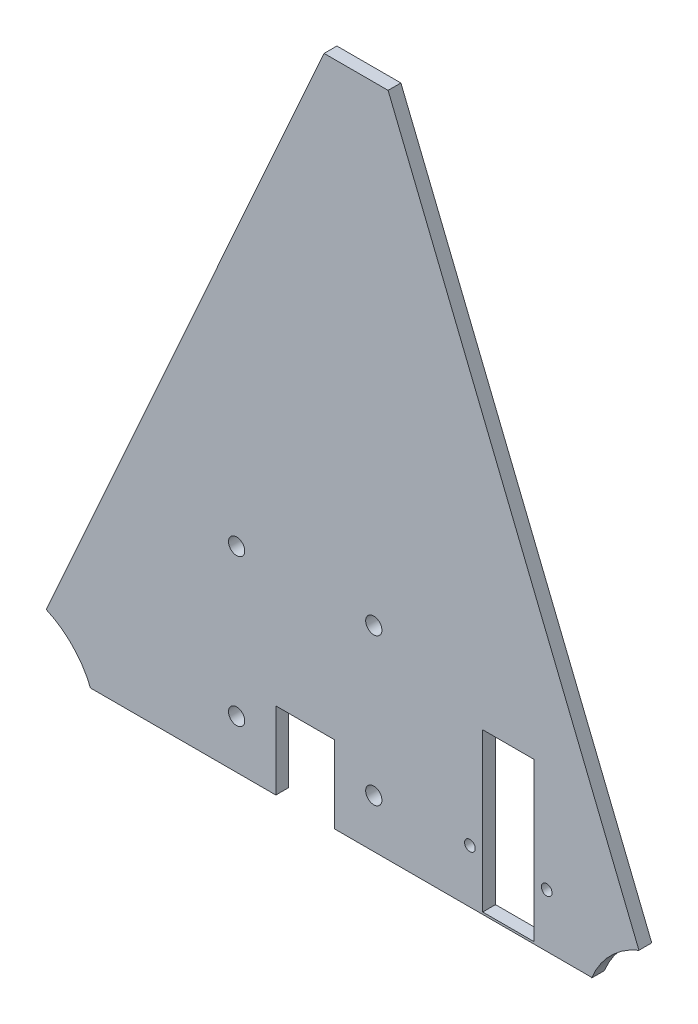
SolidWorks part; units mm, degrees
ref_plane "Front Plane" through (0, 0, 0) normal (0, 0, 1) x (1, 0, 0)
ref_plane "Top Plane" through (0, 0, 0) normal (0, 1, 0) x (1, 0, 0)
ref_plane "Right Plane" through (0, 0, 0) normal (1, 0, 0) x (0, 0, -1)
sketch "Sketch2" plane through (0, 0, 0) normal (0, 0, 1) x (1, 0, 0)
  line L0 (-189.7401, 245.3834) -> (-375.9085, -170.4146)
  line L1 (-375.9085, -170.4146) -> (16.7755, -170.4146)
  line L2 (16.7755, -170.4146) -> (-151.6401, 245.3834)
  line L4 (-189.7401, 245.3834) -> (-151.6401, 245.3834)
  dimension "D1" = 415.798
  dimension "D2" = 415.798
  dimension "D3" = 67.95
  dimension "D4" = 38.1
  dimension "D5" = 392.684
extrude "Boss-Extrude1" add sketch "Sketch2" along normal blind 7.62 contours L0 L1 L2 L4
sketch "Sketch5" plane through (0, 0, 0) normal (0, 0, -1) x (-1, 0, 0)
  circle A0 centre (375.9085, -170.4146) radius 15.875
  dimension "D1" = 31.75
extrude "Cut-Extrude2" cut sketch "Sketch5" against normal blind 50.8
sketch "Sketch6" plane through (0, 0, 0) normal (0, 0, -1) x (-1, 0, 0)
  circle A0 centre (-16.7755, -170.4146) radius 15.875
  dimension "D1" = 31.75
extrude "Cut-Extrude3" cut sketch "Sketch6" against normal blind 50.8 contours A0
ref_plane "Plane1" through (-360.0335, -170.4146, 0) normal (1, 0, 0) x (0, 0, -1)
sketch "Sketch8" plane through (0, 0, 0) normal (0, 0, -1) x (-1, 0, 0)
  line L0 (254.9716, -43.4146) -> (147.0216, -43.4146) construction
  line L1 (360.0335, -170.4146) -> (-0.9005, -170.4146) construction
  line L2 (254.9716, -170.4146) -> (254.9716, 97.7332) construction
  line L3 (254.9716, -43.4146) -> (254.9716, -170.4146) construction
  line L4 (147.0216, -43.4146) -> (147.0216, -170.4146) construction
  line L5 (147.0216, -170.4146) -> (183.5239, -170.4146) construction
  line L6 (183.5239, -170.4146) -> (183.5239, -105.3906) construction
  line L7 (170.6901, 245.3834) -> (179.5665, -170.4146) construction
  line L8 (189.7401, 245.3834) -> (151.6401, 245.3834) construction
  line L9 (183.5239, -105.3906) -> (218.4489, -105.3906) construction
  line L10 (218.4489, -105.3906) -> (218.4489, -170.4146) construction
  line L11 (218.4489, -170.4146) -> (218.4489, -105.3906)
  line L12 (218.4489, -105.3906) -> (183.5239, -105.3906)
  line L13 (183.5239, -105.3906) -> (183.5239, -170.4146)
  line L14 (153.8492, -170.4146) -> (153.8492, -48.647) construction
  dimension "D1" = 268.1478
  dimension "D2" = 107.95
  dimension "D3" = 127
  dimension "D4" = 36.5023
  dimension "D5" = 65.024
  dimension "D6" = 34.925
  dimension "D7" = 121.7676
extrude "Cut-Extrude4" cut sketch "Sketch8" against normal blind 7.62 and the other way through all contours L11 L12 L13
sketch "Sketch9" plane through (0, 0, 0) normal (0, 0, -1) x (-1, 0, 0)
  line L0 (164.9819, -122.4086) -> (183.5239, -122.4086) construction
  line L1 (183.5239, -170.4146) -> (183.5239, -105.3906) construction
  line L2 (160.1559, -127.2346) -> (160.1559, -170.4146) construction
  line L3 (183.5239, -170.4146) -> (-0.9005, -170.4146) construction
  line L4 (236.9909, -122.4086) -> (218.4489, -122.4086) construction
  line L5 (218.4489, -105.3906) -> (218.4489, -170.4146) construction
  line L6 (241.8169, -127.2346) -> (241.8169, -170.4146) construction
  line L7 (360.0335, -170.4146) -> (218.4489, -170.4146) construction
  circle A0 centre (160.1559, -122.4086) radius 4.826
  circle A1 centre (241.8169, -122.4086) radius 4.826
  dimension "D3" = 9.652
  dimension "D6" = 9.652
  dimension "D1" = 18.542
  dimension "D2" = 43.18
  dimension "D4" = 18.542
  dimension "D5" = 43.18
sketch "Sketch10" plane through (0, 0, 0) normal (0, 0, -1) x (-1, 0, 0)
  line L0 (218.4489, -110.7541) -> (349.1963, -110.7541) construction
  line L1 (218.4489, -105.3906) -> (218.4489, -170.4146) construction
  line L2 (189.7401, 245.3834) -> (369.4213, -155.9256) construction
  line L3 (7.3895, -110.7541) -> (138.1995, -110.7541) construction
  line L4 (-10.8158, -155.7008) -> (151.6401, 245.3834) construction
  line L5 (64.8263, -170.4146) -> (64.8263, -56.1146) construction
  line L8 (183.5239, -170.4146) -> (-0.9005, -170.4146) construction
  line L9 (64.8263, -56.1146) -> (95.3063, -56.1146) construction
  line L11 (95.3063, -56.1146) -> (95.3063, -170.4146) construction
  line L12 (64.8263, -170.4146) -> (64.8263, -56.1146)
  line L13 (64.8263, -56.1146) -> (95.3063, -56.1146)
  line L14 (95.3063, -56.1146) -> (95.3063, -170.4146)
  line L15 (64.8263, -170.4146) -> (95.3063, -170.4146)
  dimension "D1" = 130.7473
  dimension "D2" = 130.81
  dimension "D3" = 114.3
  dimension "D4" = 30.48
extrude "Cut-Extrude6" cut sketch "Sketch9" against normal up to next
extrude "Cut-Extrude12" cut sketch "Sketch10" against normal blind 25.4 contours L13 L14 L15 L12
sketch "Sketch13" plane through (0, 0, 0) normal (0, 0, -1) x (-1, 0, 0)
  line L0 (80.0663, -56.1146) -> (80.0663, -50.7806) construction
  line L1 (64.8263, -56.1146) -> (95.3063, -56.1146) construction
  line L2 (80.0663, -50.7806) -> (80.0663, -45.9546) construction
  circle A0 centre (80.0663, -45.9546) radius 4.826
  dimension "D3" = 9.652
  dimension "D1" = 5.334
  dimension "D2" = 4.826
sketch "Sketch14" plane through (0, 0, 0) normal (0, 0, -1) x (-1, 0, 0)
  circle A0 centre (-16.7755, -170.4146) radius 50.8
  dimension "D1" = 101.6
extrude "Cut-Extrude14" cut sketch "Sketch14" against normal up to next
sketch "Sketch15" plane through (0, 0, 0) normal (0, 0, -1) x (-1, 0, 0)
  circle A0 centre (375.9085, -170.4146) radius 50.8
  dimension "D1" = 101.6
extrude "Cut-Extrude15" cut sketch "Sketch15" against normal up to next
sketch "Sketch16" plane through (0, 0, 0) normal (0, 0, -1) x (-1, 0, 0)
  line L0 (95.3063, -56.1146) -> (95.3063, -170.4146) construction
  line L1 (95.3063, -150.0946) -> (64.8263, -150.0946)
  line L2 (95.3063, -150.0946) -> (95.3063, -170.4146)
  line L3 (95.3063, -170.4146) -> (64.8263, -170.4146)
  line L4 (64.8263, -150.0946) -> (64.8263, -170.4146)
  dimension "D1" = 20.32
extrude "Boss-Extrude2" add sketch "Sketch16" against normal blind 7.62
sketch "Sketch17" plane through (0, 0, 0) normal (0, 0, -1) x (-1, 0, 0)
  line L0 (64.8263, -150.0946) -> (64.8263, -125.9646) construction
  line L1 (64.8263, -150.0946) -> (64.8263, -56.1146) construction
  line L2 (64.8263, -125.9646) -> (64.8263, -113.2646) construction
  line L3 (64.8263, -113.2646) -> (49.5863, -113.2646) construction
  line L4 (49.5863, -113.2646) -> (49.5863, -125.9646) construction
  line L5 (49.5863, -125.9646) -> (64.8263, -125.9646) construction
  line L6 (49.5863, -119.6146) -> (64.8263, -119.6146) construction
  line L7 (95.3063, -113.2646) -> (110.5463, -113.2646) construction
  line L8 (95.3063, -56.1146) -> (95.3063, -150.0946) construction
  line L9 (110.5463, -113.2646) -> (110.5463, -125.9646) construction
  line L10 (110.5463, -125.9646) -> (95.3063, -125.9646) construction
  line L11 (110.5463, -119.6146) -> (95.3063, -119.6146) construction
  circle A0 centre (57.2063, -119.6146) radius 3.175
  circle A3 centre (102.9263, -119.6146) radius 3.175
  dimension "D4" = 6.35
  dimension "D7" = 6.35
  dimension "D1" = 24.13
  dimension "D2" = 12.7
  dimension "D3" = 15.24
  dimension "D5" = 15.24
  dimension "D6" = 12.7
extrude "Cut-Extrude16" cut sketch "Sketch17" against normal up to next
sketch "Sketch18" plane through (0, 0, 0) normal (0, 0, -1) x (-1, 0, 0)
  line L5 (30.4451, -170.4146) -> (331.0546, -170.4146)
  line L6 (30.4451, -170.4146) -> (30.4451, -151.3646)
  line L7 (30.4451, -151.3646) -> (331.0546, -151.3646)
  line L8 (331.0546, -170.4146) -> (331.0546, -151.3646)
  dimension "D1" = 19.05
extrude "Cut-Extrude17" cut sketch "Sketch18" against normal up to next contours L7 L8 L5 L6
sketch "Sketch19" plane through (0, 0, 0) normal (0, 0, -1) x (-1, 0, 0)
  line L0 (241.8169, -122.4086) -> (241.8169, -34.7786) construction
  line L1 (160.1559, -122.4086) -> (160.1559, -34.7786) construction
  circle A0 centre (241.8169, -34.7786) radius 4.826
  circle A1 centre (160.1559, -34.7786) radius 4.826
  dimension "D3" = 9.652
  dimension "D4" = 9.652
  dimension "D1" = 87.63
  dimension "D2" = 87.63
extrude "Cut-Extrude18" cut sketch "Sketch19" against normal up to next
